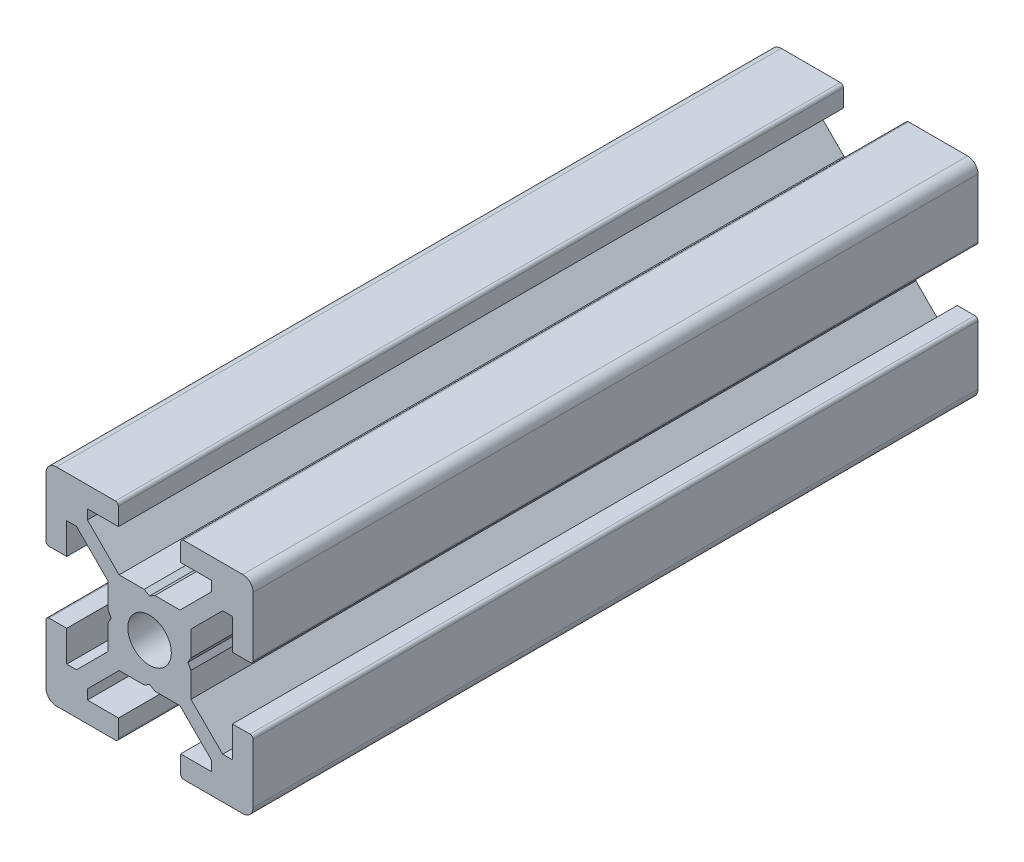
SolidWorks part; units mm, degrees
ref_plane "Front Plane" through (0, 0, 0) normal (0, 0, 1) x (1, 0, 0)
ref_plane "Top Plane" through (0, 0, 0) normal (0, 1, 0) x (1, 0, 0)
ref_plane "Right Plane" through (0, 0, 0) normal (1, 0, 0) x (0, 0, -1)
ref_plane "Plane1" through (0, 0, 0) normal (0, 0, 1) x (1, 0, 0)
sketch "Sketch1" plane through (0, 0, 0) normal (0, 0, 1) x (1, 0, 0)
  line L0 (-10, 9) -> (-10, 3.3)
  line L1 (-9.7, 3) -> (-8, 3)
  line L2 (-8, 3) -> (-8, 6)
  line L3 (-8, 6) -> (-7.0607, 6)
  line L4 (-7.0607, 6) -> (-4, 2.9393)
  line L5 (-4, 2.9393) -> (-4, 0.5196)
  line L6 (-4, 0.5196) -> (-3.7, 0)
  line L7 (-3.7, 0) -> (-4, -0.5196)
  line L8 (-4, -0.5196) -> (-4, -2.9393)
  line L9 (-4, -2.9393) -> (-7.0607, -6)
  line L10 (-7.0607, -6) -> (-8, -6)
  line L11 (-8, -6) -> (-8, -3)
  line L12 (-8, -3) -> (-9.7, -3)
  line L13 (-10, -3.3) -> (-10, -9)
  line L14 (-9, -10) -> (-3.3, -10)
  line L15 (-3, -9.7) -> (-3, -8)
  line L16 (-3, -8) -> (-6, -8)
  line L17 (-6, -8) -> (-6, -7.0607)
  line L18 (-6, -7.0607) -> (-2.9393, -4)
  line L19 (-2.9393, -4) -> (-0.5196, -4)
  line L20 (-0.5196, -4) -> (0, -3.7)
  line L21 (0, -3.7) -> (0.5196, -4)
  line L22 (0.5196, -4) -> (2.9393, -4)
  line L23 (2.9393, -4) -> (6, -7.0607)
  line L24 (6, -7.0607) -> (6, -8)
  line L25 (6, -8) -> (3, -8)
  line L26 (3, -8) -> (3, -9.7)
  line L27 (3.3, -10) -> (9, -10)
  line L28 (10, -9) -> (10, -3.3)
  line L29 (9.7, -3) -> (8, -3)
  line L30 (8, -3) -> (8, -6)
  line L31 (8, -6) -> (7.0606, -6)
  line L32 (7.0606, -6) -> (4, -2.9393)
  line L33 (4, -2.9393) -> (4, -0.5196)
  line L34 (4, -0.5196) -> (3.7, 0)
  line L35 (3.7, 0) -> (4, 0.5196)
  line L36 (4, 0.5196) -> (4, 2.9393)
  line L37 (4, 2.9393) -> (7.0607, 6)
  line L38 (7.0607, 6) -> (8, 6)
  line L39 (8, 6) -> (8, 3)
  line L40 (8, 3) -> (9.7, 3)
  line L41 (10, 3.3) -> (10, 9)
  line L42 (9, 10) -> (3.3, 10)
  line L43 (3, 9.7) -> (3, 8)
  line L44 (3, 8) -> (6, 8)
  line L45 (6, 8) -> (6, 7.0607)
  line L46 (6, 7.0607) -> (2.9393, 4)
  line L47 (2.9393, 4) -> (0.5196, 4)
  line L48 (0.5196, 4) -> (0, 3.7)
  line L49 (0, 3.7) -> (-0.5196, 4)
  line L50 (-0.5196, 4) -> (-2.9394, 4)
  line L51 (-2.9394, 4) -> (-6, 7.0606)
  line L52 (-6, 7.0606) -> (-6, 8)
  line L53 (-6, 8) -> (-3, 8)
  line L54 (-3, 8) -> (-3, 9.7)
  line L55 (-3.3, 10) -> (-9, 10)
  arc A0 (-10, 3.3) -> (-9.7, 3) centre (-9.7, 3.3) ccw
  arc A1 (-9.7, -3) -> (-10, -3.3) centre (-9.7, -3.3) ccw
  arc A2 (-10, -9) -> (-9, -10) centre (-9, -9) ccw
  arc A3 (-3.3, -10) -> (-3, -9.7) centre (-3.3, -9.7) ccw
  arc A4 (3, -9.7) -> (3.3, -10) centre (3.3, -9.7) ccw
  arc A5 (9, -10) -> (10, -9) centre (9, -9) ccw
  arc A6 (10, -3.3) -> (9.7, -3) centre (9.7, -3.3) ccw
  arc A7 (9.7, 3) -> (10, 3.3) centre (9.7, 3.3) ccw
  arc A8 (10, 9) -> (9, 10) centre (9, 9) ccw
  arc A9 (3.3, 10) -> (3, 9.7) centre (3.3, 9.7) ccw
  arc A10 (-3, 9.7) -> (-3.3, 10) centre (-3.3, 9.7) ccw
  arc A11 (-9, 10) -> (-10, 9) centre (-9, 9) ccw
extrude "Boss-Extrude1" add sketch "Sketch1" against normal blind 70
ref_plane "Plane2" through (0, 0, 0) normal (1, 0, 0) x (0, 0, -1)
sketch "Sketch2" plane through (0, 0, 0) normal (1, 0, 0) x (0, 0, -1)
  line L0 (0, 0) -> (0, 2.1)
  line L1 (0, 2.1) -> (400, 2.1)
  line L2 (400, 2.1) -> (400, 0)
  line L3 (400, 0) -> (0, 0)
  line L4 (400, 0) -> (0, 0) construction
revolve "Cut-Revolve1" cut sketch "Sketch2" angle 360 about L4
